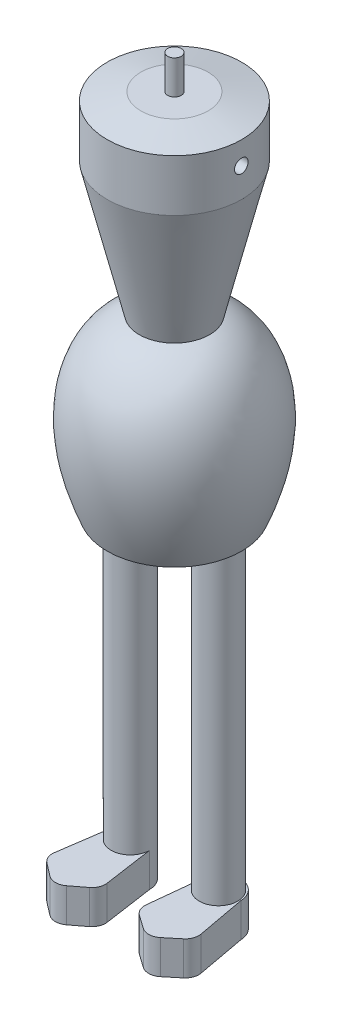
SolidWorks part; units mm, degrees
ref_plane "Front Plane" through (0, 0, 0) normal (0, 0, 1) x (1, 0, 0)
ref_plane "Top Plane" through (0, 0, 0) normal (0, 1, 0) x (1, 0, 0)
ref_plane "Right Plane" through (0, 0, 0) normal (1, 0, 0) x (0, 0, -1)
sketch "Sketch1" plane through (0, 0, 0) normal (0, 0, 1) x (1, 0, 0)
  line L0 (0, 53.6546) -> (0, -62.9305) construction
  line L1 (-5.1836, 0) -> (5.1836, 0)
  line L2 (5.1836, 0) -> (9.9125, 19.6431)
  line L3 (9.9125, 19.6431) -> (9.9125, 27.282)
  line L4 (9.9125, 27.282) -> (4.9562, 28.4752)
  line L5 (4.9562, -25.2813) -> (0, -25.2813)
  line L15 (-4.9562, -25.2813) -> (0, -25.2813)
  line L16 (-9.9125, 27.282) -> (-4.9562, 28.4752)
  line L17 (-9.9125, 19.6431) -> (-9.9125, 27.282)
  line L18 (-5.1836, 0) -> (-9.9125, 19.6431)
  line L20 (-9.9125, -25.2813) -> (-4.9562, -25.2813)
  line L21 (4.9562, -25.2813) -> (9.9125, -25.2813)
  line L22 (-4.9562, 28.4752) -> (4.9562, 28.4752)
  spline S0 degree 3 poles (5.1836, 0) (8.574, -1.1889) (14.4922, -9.3926) (12.1772, -19.841) (9.9125, -25.2813) knots 0 0 0 0 0.353823 1 1 1 1
  spline S5 degree 3 poles (-5.1836, 0) (-8.574, -1.1889) (-14.4922, -9.3926) (-12.1772, -19.841) (-9.9125, -25.2813) knots 0 0 0 0 0.353823 1 1 1 1
revolve "Revolve7" add sketch "Sketch1" angle 360 about L0
sketch "Sketch2" plane through (0, -25.2813, 0) normal (0, -1, 0) x (1, 0, 0)
  line L0 (0, 7.5513) -> (0, -7.3596) construction
  circle A0 centre (-6.4971, 0) radius 2.8337
  circle A1 centre (6.4971, 0) radius 2.8337
extrude "Boss-Extrude1" add sketch "Sketch2" along normal blind 45
sketch "Sketch3" plane through (0, -70.2813, 0) normal (0, -1, 0) x (1, 0, 0)
  line L0 (-9.3308, 0) -> (-10.5603, 8.4712)
  line L1 (-10.5603, 8.4712) -> (-6.4971, 11.576)
  line L2 (-6.4971, 14.7192) -> (-6.4971, -4.4081) construction
  line L3 (-3.6635, 0) -> (-2.434, 8.4712)
  line L4 (-2.434, 8.4712) -> (-6.4971, 11.576)
  line L5 (0.3641, 14.7192) -> (0, -3.9864) construction
  line L6 (2.917, 8.367) -> (7.0979, 11.3114)
  line L7 (3.8159, -0.1456) -> (2.917, 8.367)
  line L8 (11.0371, 8.0508) -> (7.0979, 11.3114)
  line L9 (9.4789, -0.3662) -> (11.0371, 8.0508)
  circle A0 centre (-6.4971, 0) radius 2.8337 construction
  circle A1 centre (-6.4971, 0) radius 2.8337 construction
  arc A2 (-9.3308, 0) -> (-3.6635, 0) centre (-6.4971, 0) ccw
  arc A3 (9.4789, -0.3662) -> (3.8159, -0.1456) centre (6.6474, -0.2559) cw
extrude "Boss-Extrude2" add sketch "Sketch3" along normal blind 5
fillet "Fillet1" radius 2 2 edges at (7.0979, -72.7813, 11.3114) (-6.4971, -72.7813, 11.576)
fillet "Fillet2" radius 2 4 edges at (11.0371, -72.7813, 8.0508) (2.917, -72.7813, 8.367) (-10.5603, -72.7813, 8.4712) (-2.434, -72.7813, 8.4712)
sketch "Sketch5" plane through (0, 0, 0) normal (1, 0, 0) x (0, 0, -1)
  circle A0 centre (0, 23.9363) radius 1
extrude "Cut-Extrude2" cut sketch "Sketch5" against normal blind 96 and the other way blind 115
sketch "Sketch6" plane through (0, 0, 0) normal (0, 0, 1) x (1, 0, 0)
  line L0 (4.9562, 28.4752) -> (-4.9562, 28.4752) construction
  circle A0 centre (0, 23.79) radius 0.9982
  circle A1 centre (0, 10.29) radius 1
sketch "Sketch7" plane through (0, 28.4752, 0) normal (0, 1, 0) x (1, 0, 0)
  circle A0 centre (0, 0) radius 1
extrude "Boss-Extrude3" add sketch "Sketch7" along normal blind 5
